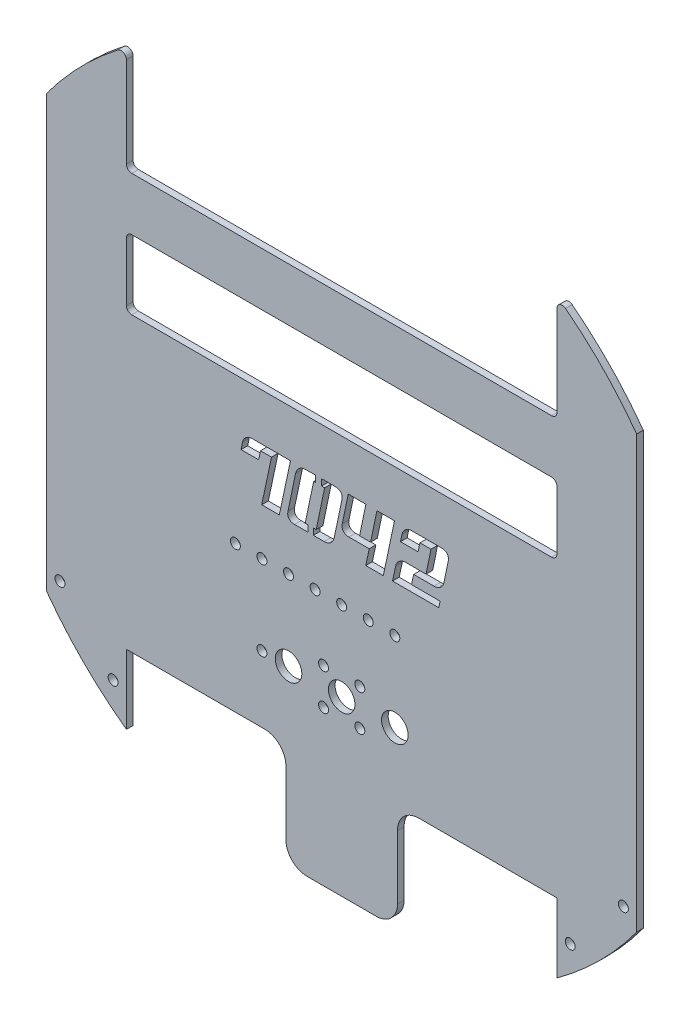
SolidWorks part; units mm, degrees
material "6061 Alloy"
ref_plane "Front Plane" through (0, 0, 0) normal (0, 0, 1) x (1, 0, 0)
ref_plane "Top Plane" through (0, 0, 0) normal (0, 1, 0) x (1, 0, 0)
ref_plane "Right Plane" through (0, 0, 0) normal (1, 0, 0) x (0, 0, -1)
sketch "Sketch1" plane through (0, 0, 0) normal (0, 0, 1) x (1, 0, 0)
  line L1 (-140.9655, 145.0225) -> (-102.8655, 145.0225)
  line L2 (-140.9655, 145.0225) -> (-140.9655, -145.0225)
  line L3 (-140.9655, -145.0225) -> (-102.8655, -145.0225)
  line L4 (-102.8655, 145.0225) -> (-102.8655, -145.0225)
  line L5 (-140.9655, 145.0225) -> (-102.8655, -145.0225) construction
  line L6 (-140.9655, -145.0225) -> (-102.8655, 145.0225) construction
  line L7 (-140.9655, 31.75) -> (140.9655, 31.75)
  line L8 (-140.9655, 31.75) -> (-140.9655, -31.75)
  line L9 (-140.9655, -31.75) -> (140.9655, -31.75)
  line L10 (140.9655, 31.75) -> (140.9655, -31.75)
  line L11 (-140.9655, 31.75) -> (140.9655, -31.75) construction
  line L12 (-140.9655, -31.75) -> (140.9655, 31.75) construction
  line L13 (102.8655, 145.0225) -> (140.9655, 145.0225)
  line L14 (102.8655, 145.0225) -> (102.8655, -145.0225)
  line L15 (102.8655, -145.0225) -> (140.9655, -145.0225)
  line L16 (140.9655, 145.0225) -> (140.9655, -145.0225)
  line L17 (102.8655, 145.0225) -> (140.9655, -145.0225) construction
  line L18 (102.8655, -145.0225) -> (140.9655, 145.0225) construction
  line L19 (-140.9655, -31.75) -> (140.9655, -31.75)
  line L20 (-140.9655, -31.75) -> (-140.9655, -69.85)
  line L21 (-140.9655, -69.85) -> (140.9655, -69.85)
  line L22 (140.9655, -31.75) -> (140.9655, -69.85)
  circle A0 centre (0, 0) radius 177.8
  circle A7 centre (0, -38.1) radius 25.4 construction
  circle A8 centre (-25.4, -38.1) radius 2.3813
  circle A9 centre (25.4, -38.1) radius 2.3813
  circle A10 centre (0, -38.1) radius 2.3812
  point P3 (-121.9155, 0)
  point P12 (121.9155, 0)
  dimension "D1" = 355.6
  dimension "D5" = 50.8
  dimension "D6" = 38.1
  dimension "D7" = 281.9311
  dimension "D10" = 4.7625
  dimension "D8" = 4.7625
  dimension "D9" = 4.7625
  dimension "D2" = 38.1
  dimension "D3" = 38.1
  dimension "D4" = 63.5
  dimension "D12" = 38.1
extrude "Boss-Extrude1" add sketch "Sketch1" along normal blind 3.175
sketch "Sketch2" plane through (0, 0, 3.175) normal (0, 0, 1) x (1, 0, 0)
  line L0 (-140.9655, -103.066) -> (-140.9655, -108.3585)
  line L1 (-140.9655, 108.3585) -> (-140.9655, -108.3585) construction
  line L2 (-102.8655, -141.1119) -> (-102.8655, -145.0225)
  line L3 (102.8655, -141.1119) -> (102.8655, -145.0225)
  line L4 (102.8655, -69.85) -> (102.8655, -145.0225) construction
  line L5 (140.9655, -103.066) -> (140.9655, -108.3585)
  line L6 (140.9655, 108.3585) -> (140.9655, -108.3585) construction
  line L7 (-102.8655, -69.85) -> (-102.8655, -145.0225) construction
  circle A0 centre (0, 0) radius 177.8
  circle A1 centre (0, 0) radius 174.625
  line M3 (-140.9655, 108.3585) -> (-140.9655, -108.3585)
  arc M4 (-140.9655, -108.3585) -> (-102.8655, -145.0225) centre (0, 0) ccw
  line M5 (-102.8655, -145.0225) -> (-102.8655, -69.85)
  line M7 (102.8655, -69.85) -> (102.8655, -145.0225)
  arc M8 (102.8655, -145.0225) -> (140.9655, -108.3585) centre (0, 0) ccw
  line M9 (140.9655, -108.3585) -> (140.9655, 108.3585)
  dimension "D1" = 355.6
  dimension "D2" = 349.25
extrude "Boss-Extrude2" add sketch "Sketch2" along normal blind 50.8 contours A1 M3 M4 M5 | A1 M7 M8 M9
sketch "Sketch3" plane through (0, 0, 3.175) normal (0, 0, 1) x (1, 0, 0)
  circle A0 centre (0, 0) radius 174.625
  circle A1 centre (0, 0) radius 203.8293
  dimension "D1" = 349.25
extrude "Cut-Extrude1" cut sketch "Sketch3" along normal through all and the other way through all
sketch "Sketch5" plane through (0, 0, 3.175) normal (0, 0, 1) x (1, 0, 0)
  line L0 (0, 165.1) -> (0, -165.1) construction
  line L1 (102.8655, -69.85) -> (102.8655, -141.1119) construction
  circle A0 centre (0, 0) radius 165.1 construction
  circle A1 centre (134.6155, -95.5859) radius 2.3813
  circle A2 centre (109.2155, -123.8143) radius 2.3813
  circle A3 centre (-134.6155, -95.5859) radius 2.3813
  circle A4 centre (-109.2155, -123.8143) radius 2.3813
  arc A5 (140.9655, 103.066) -> (102.8655, 141.1119) centre (0, 0) ccw construction
  dimension "D1" = 330.2
  dimension "D3" = 4.7625
  dimension "D4" = 4.7625
  dimension "D2" = 25.4
  dimension "D5" = 6.35
extrude "Cut-Extrude3" cut sketch "Sketch5" against normal through all
sketch "Sketch6" plane through (0, 0, 3.175) normal (0, 0, 1) x (1, 0, 0)
  line L0 (-102.8655, 141.1119) -> (-102.8655, 31.75) construction
  line L1 (-102.8655, 90.3119) -> (102.8655, 90.3119)
  line L2 (-102.8655, 90.3119) -> (-102.8655, 64.9119)
  line L3 (-102.8655, 64.9119) -> (102.8655, 64.9119)
  line L4 (102.8655, 90.3119) -> (102.8655, 64.9119)
  line L5 (102.8655, 141.1119) -> (102.8655, 31.75) construction
  dimension "D1" = 25.4
  dimension "D2" = 50.8
extrude "Boss-Extrude3" add sketch "Sketch6" against normal blind 3.175
sketch "Sketch7" plane through (0, 0, 3.175) normal (0, 0, 1) x (1, 0, 0)
  line L0 (102.8655, 90.3119) -> (-102.8655, 90.3119) construction
  line L1 (-157.8266, 90.3119) -> (153.0605, 90.3119)
  line L2 (-157.8266, 90.3119) -> (-157.8266, 162.3702)
  line L3 (-157.8266, 162.3702) -> (153.0605, 162.3702)
  line L4 (153.0605, 90.3119) -> (153.0605, 162.3702)
extrude "Cut-Extrude4" [suppressed] cut sketch "Sketch7" against normal through all
sketch "Sketch8" plane through (0, 0, 3.175) normal (0, 0, 1) x (1, 0, 0)
  circle A0 centre (0, -38.1) radius 38.1 construction
  circle A1 centre (-38.1, -38.1) radius 2.3812
  circle A2 centre (0, -38.1) radius 50.8 construction
  circle A3 centre (-50.8, -38.1) radius 2.3812
  circle A4 centre (0, -38.1) radius 12.7 construction
  circle A5 centre (12.7, -38.1) radius 2.3812
  circle A6 centre (-12.7, -38.1) radius 2.3812
  point P13 (0, 0)
  point P16 (0, 0)
  dimension "D1" = 76.2
  dimension "D2" = 4.7625
  dimension "D3" = 101.6
  dimension "D4" = 4.7625
  dimension "D5" = 25.4
  dimension "D6" = 4.7625
  dimension "D7" = 4.7625
extrude "Cut-Extrude5" cut sketch "Sketch8" against normal through all
sketch "Sketch9" plane through (0, 0, 3.175) normal (0, 0, 1) x (1, 0, 0)
  line L0 (102.8655, -69.85) -> (102.8655, -141.1119) construction
  line L1 (-102.8655, -69.85) -> (102.8655, -69.85)
  line L2 (-102.8655, -69.85) -> (-102.8655, -107.95)
  line L3 (-102.8655, -107.95) -> (102.8655, -107.95)
  line L4 (102.8655, -69.85) -> (102.8655, -107.95)
  dimension "D1" = 38.1
extrude "Boss-Extrude4" add sketch "Sketch9" against normal blind 3.175
sketch "Sketch10" plane through (0, 0, 3.175) normal (0, 0, 1) x (1, 0, 0)
  circle A0 centre (0, -76.2) radius 6.35
  circle A1 centre (0, -38.1) radius 2.3812 construction
  circle A2 centre (0, -76.2) radius 25.4 construction
  circle A3 centre (0, -76.2) radius 38.1 construction
  circle A4 centre (-25.4, -76.2) radius 2.3813
  circle A5 centre (-38.1, -76.2) radius 2.3812
  circle A6 centre (25.4, -76.2) radius 2.3813
  dimension "D1" = 38.1
  dimension "D2" = 12.7
  dimension "D3" = 50.8
  dimension "D4" = 76.2
  dimension "D5" = 4.7625
  dimension "D6" = 4.7625
  dimension "D7" = 4.7625
extrude "Cut-Extrude6" cut sketch "Sketch10" against normal through all
sketch "Sketch11" plane through (0, 0, 3.175) normal (0, 0, 1) x (1, 0, 0)
  line L0 (-102.8655, -107.95) -> (102.8655, -107.95) construction
  line L1 (-26.6655, -107.95) -> (26.6655, -107.95)
  line L2 (-26.6655, -107.95) -> (-26.6655, -158.75)
  line L3 (-26.6655, -158.75) -> (26.6655, -158.75)
  line L4 (26.6655, -107.95) -> (26.6655, -158.75)
  line L5 (-102.8655, -107.95) -> (-102.8655, -141.1119) construction
  line L6 (102.8655, -107.95) -> (102.8655, -141.1119) construction
  dimension "D1" = 50.8
  dimension "D2" = 76.2
  dimension "D3" = 76.2
extrude "Boss-Extrude5" add sketch "Sketch11" against normal blind 3.175
fillet "Fillet1" radius 10.16 4 edges at (26.6655, -107.95, 1.5875) (-26.6655, -107.95, 1.5875) (-26.6655, -158.75, 1.5875) (26.6655, -158.75, 1.5875)
sketch "Sketch12" plane through (0, 0, 3.175) normal (0, 0, 1) x (1, 0, 0)
  line L1 (-12.7, -63.5) -> (12.7, -63.5) construction
  line L2 (-12.7, -63.5) -> (-12.7, -88.9) construction
  line L3 (-12.7, -88.9) -> (12.7, -88.9) construction
  line L4 (12.7, -63.5) -> (12.7, -88.9) construction
  circle A0 centre (-25.4, -76.2) radius 6.35
  circle A1 centre (25.4, -76.2) radius 6.35
  circle A2 centre (0, -76.2) radius 6.35 construction
  circle A3 centre (-8.6678, -67.5323) radius 2.3812
  circle A7 centre (8.6677, -67.5322) radius 2.3813
  circle A8 centre (8.6678, -84.8677) radius 2.3812
  circle A9 centre (-8.6677, -84.8677) radius 2.3812
  point P23 (0, -76.2)
  point P24 (0, -76.2)
  dimension "D1" = 12.7
  dimension "D2" = 12.7
  dimension "D7" = 4.0323
  dimension "D9" = 4.7625
  dimension "D3" = 12.7
  dimension "D4" = 25.4
  dimension "D5" = 12.7
  dimension "D6" = 25.4
  dimension "D8" = 4.0323
  dimension "D10" = 4
extrude "Cut-Extrude7" cut sketch "Sketch12" against normal through all
fillet "Fillet2" radius 2.54 2 edges at (102.8655, 141.1119, 1.5875) (-102.8655, 141.1119, 1.5875)
sketch "Sketch13" plane through (0, 0, 3.175) normal (0, 0, 1) x (1, 0, 0)
  line L0 (-140.9655, -16.1069) -> (140.9655, -16.1069) construction
  line L1 (-140.9655, 103.066) -> (-140.9655, -103.066) construction
  line L2 (140.9655, 103.066) -> (140.9655, -103.066) construction
  text T0 "7042" font "Aero" height 25.4
extrude "Cut-Extrude8" cut sketch "Sketch13" against normal through all
sketch "Sketch14" plane through (0, 0, 3.175) normal (0, 0, 1) x (1, 0, 0)
  line L1 (-12.3972, 11.8715) -> (-9.6379, 11.8715)
  line L2 (-12.3972, 11.8715) -> (-12.3972, 3.9079)
  line L3 (-12.3972, 3.9079) -> (-9.6379, 3.9079)
  line L4 (-9.6379, 11.8715) -> (-9.6379, 3.9079)
  line L5 (-16.0587, -11.8105) -> (-13.5317, -11.8105)
  line L6 (-16.0587, -11.8105) -> (-16.0587, -17.7494)
  line L7 (-16.0587, -17.7494) -> (-13.5317, -17.7494)
  line L8 (-13.5317, -11.8105) -> (-13.5317, -17.7494)
extrude "Boss-Extrude6" add sketch "Sketch14" against normal blind 3.175
fillet "Fillet3" radius 2.54 6 edges at (-102.8655, 90.3119, 1.5875) (102.8655, 90.3119, 1.5875) (102.8655, 31.75, 1.5875) (102.8655, 64.9119, 1.5875) (-102.8655, 31.75, 1.5875) (-102.8655, 64.9119, 1.5875)
